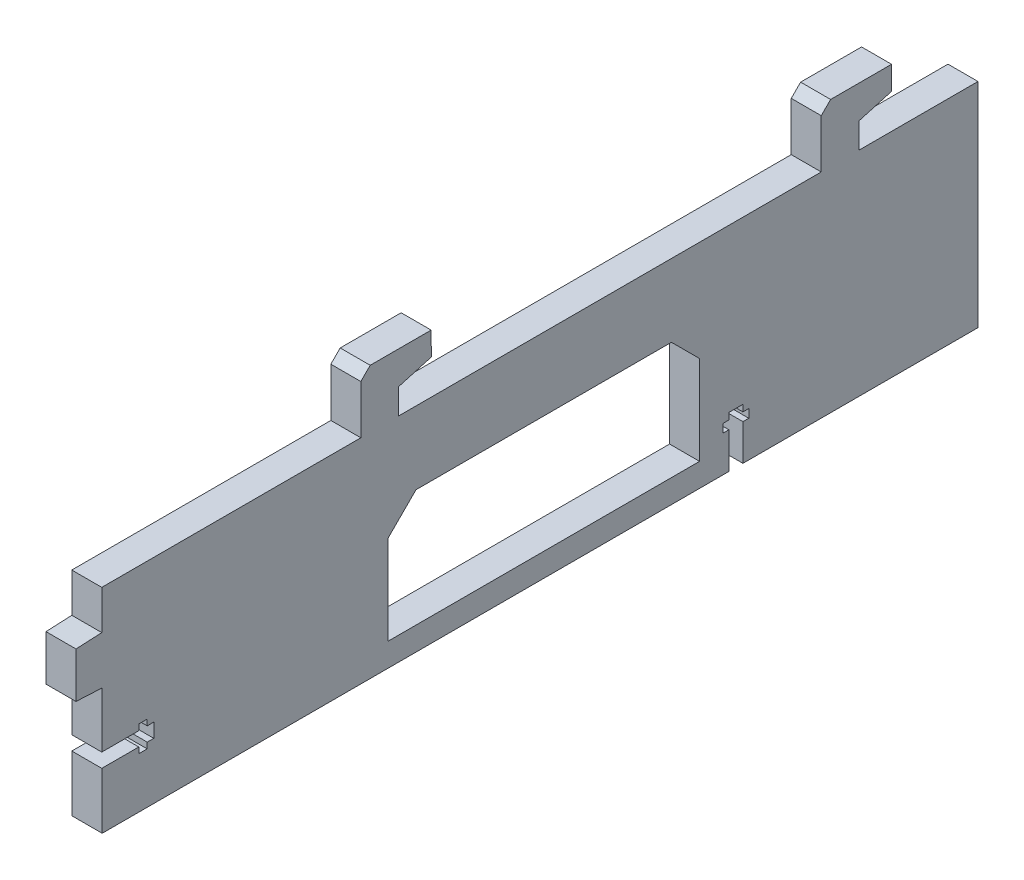
SolidWorks part; units mm, degrees
ref_plane "Front Plane" through (0, 0, 0) normal (0, 0, 1) x (1, 0, 0)
ref_plane "Top Plane" through (0, 0, 0) normal (0, 1, 0) x (1, 0, 0)
ref_plane "Right Plane" through (0, 0, 0) normal (1, 0, 0) x (0, 0, -1)
sketch "Sketch1" plane through (0, 0, 0) normal (1, 0, 0) x (0, 0, -1)
  line L0 (7.6995, 16.2993) -> (7.6995, 15.0507)
  line L1 (10.8995, 12.0493) -> (9.4995, 12.0493)
  line L2 (10.8995, 15.0507) -> (9.4995, 15.0507)
  line L3 (63.115, 45.4894) -> (63.115, 50.9)
  line L4 (57.075, 57.8874) -> (70.0794, 57.8874)
  line L5 (161.345, 45.4894) -> (186.745, 45.4894)
  line L6 (0, 0) -> (-0.1908, 0.0878)
  line L7 (10.8995, 12.0493) -> (10.8995, 15.0507)
  line L8 (70.0794, 57.8874) -> (70.115, 52.89)
  line L9 (57.075, 57.8874) -> (55.075, 55.8874)
  line L10 (70.115, 52.89) -> (63.115, 50.9)
  line L11 (0, 0) -> (73.8424, 0)
  line L12 (55.075, 55.8874) -> (55.075, 45.49)
  line L13 (63.115, 45.4894) -> (153.305, 45.4901)
  line L14 (60.8424, 5) -> (127.3424, 5)
  line L15 (168.3094, 57.8874) -> (168.345, 52.89)
  line L16 (155.305, 57.8874) -> (168.3094, 57.8874)
  line L17 (7.6995, 15.0507) -> (-0.1908, 15.0507)
  line L18 (153.305, 55.8874) -> (153.305, 45.4901)
  line L19 (155.305, 57.8874) -> (153.305, 55.8874)
  line L20 (161.345, 45.4894) -> (161.345, 50.9)
  line L21 (186.745, 45.4894) -> (186.7481, 0)
  line L22 (-0.1908, 45.49) -> (55.075, 45.49)
  line L23 (9.4995, 12.0493) -> (9.4995, 10.7993)
  line L24 (9.4995, 16.2993) -> (7.6995, 16.2993)
  line L25 (168.345, 52.89) -> (161.345, 50.9)
  line L26 (132.3481, 7.7113) -> (133.5967, 7.7113)
  line L27 (136.5981, 10.9113) -> (136.5981, 9.5113)
  line L28 (133.5967, 10.9113) -> (133.5967, 9.5113)
  line L29 (136.5981, 10.9113) -> (133.5967, 10.9113)
  line L30 (136.5981, 7.7113) -> (136.5981, 0)
  line L31 (136.5981, 9.5113) -> (137.8481, 9.5113)
  line L32 (132.3481, 9.5113) -> (132.3481, 7.7113)
  line L33 (133.5967, 7.7113) -> (133.5967, 0)
  line L34 (-5.6921, 27.1523) -> (-0.1908, 26.8758)
  line L35 (7.6995, 12.0493) -> (-0.1908, 12.0493)
  line L36 (7.6995, 10.7993) -> (7.6995, 12.0493)
  line L37 (137.8481, 7.7113) -> (136.5981, 7.7113)
  line L38 (137.8481, 9.5113) -> (137.8481, 7.7113)
  line L39 (132.3481, 9.5113) -> (133.5967, 9.5113)
  line L40 (136.5981, 0) -> (186.7481, 0)
  line L41 (-0.1908, 15.0507) -> (-0.1908, 26.8758)
  line L42 (-0.1908, 0.0878) -> (-0.1908, 12.0493)
  line L43 (9.4995, 10.7993) -> (7.6995, 10.7993)
  line L44 (-0.1908, 37.1258) -> (-0.1908, 45.49)
  line L45 (-5.6895, 36.8523) -> (-0.1908, 37.1258)
  line L46 (-5.6895, 36.8523) -> (-5.6921, 27.1523)
  line L47 (9.4995, 16.2993) -> (9.4995, 15.0507)
  line L48 (118.8424, 0) -> (133.5967, 0)
  line L49 (118.8424, 0) -> (73.8424, 0)
  line L50 (127.3424, 5) -> (127.3424, 24)
  line L51 (121.3424, 30) -> (66.8424, 30)
  line L52 (60.8424, 5) -> (60.8424, 24)
  line L54 (60.8424, 32.9008) -> (66.8424, 32.9008) construction
  line L55 (66.8424, 30) -> (60.8424, 24)
  line L56 (94.0924, 30) -> (94.0924, 5) construction
  line L57 (121.3424, 30) -> (127.3424, 24)
  dimension "D2" = 6
  dimension "D4" = 45
extrude "Boss-Extrude1" add sketch "Sketch1" along normal blind 6.4
